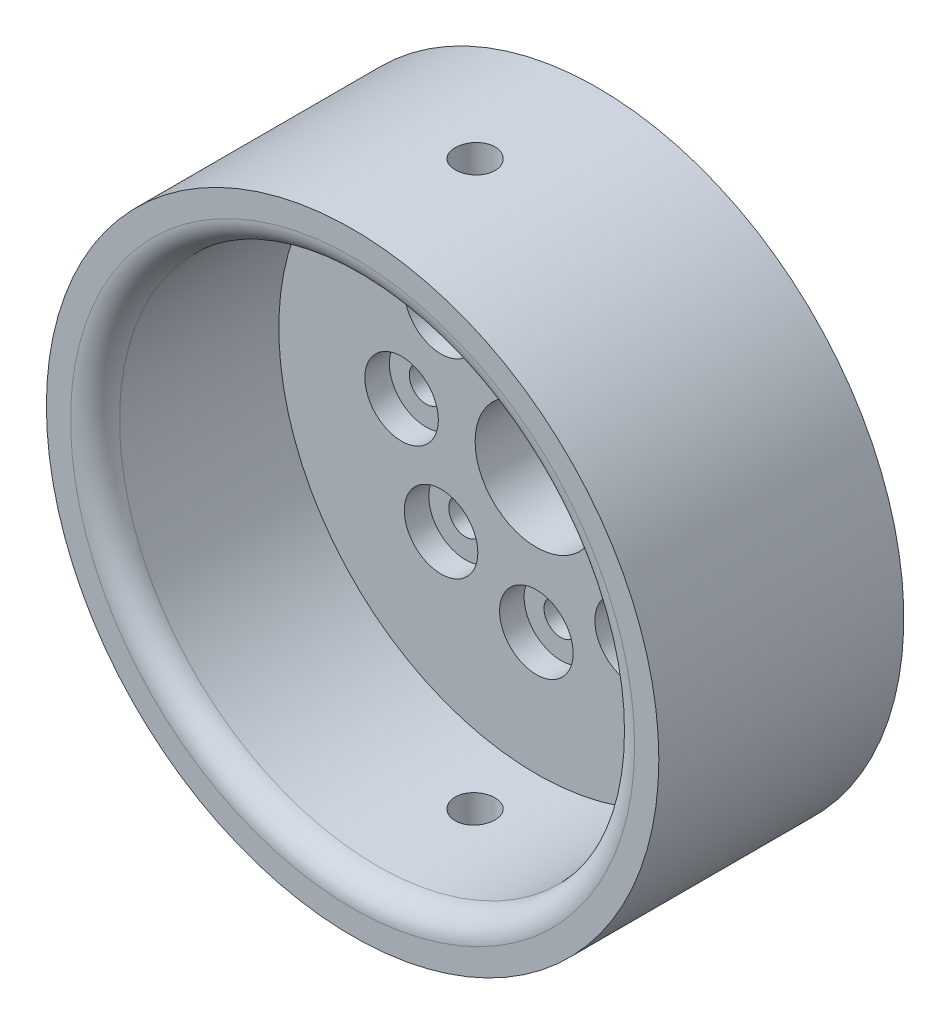
SolidWorks part; units mm, degrees
ref_plane "Front Plane" through (0, 0, 0) normal (0, 0, 1) x (1, 0, 0)
ref_plane "Top Plane" through (0, 0, 0) normal (0, 1, 0) x (1, 0, 0)
ref_plane "Right Plane" through (0, 0, 0) normal (1, 0, 0) x (0, 0, -1)
sketch "Sketch1" plane through (0, 0, 0) normal (0, 0, 1) x (1, 0, 0)
  circle A0 centre (0, 0) radius 20.15
  circle A1 centre (0, 0) radius 25
  dimension "D1" = 40.3
  dimension "D2" = 50
extrude "Boss-Extrude1" add sketch "Sketch1" along normal blind 10
sketch "Sketch2" plane through (0, 0, 0) normal (0, 0, -1) x (-1, 0, 0)
  circle A0 centre (0, 0) radius 11
  circle A1 centre (-11, 0) radius 1.375
  circle A2 centre (-7.7782, 7.7782) radius 1.375
  circle A3 centre (0, 11) radius 1.375
  circle A4 centre (7.7782, 7.7782) radius 1.375
  circle A5 centre (11, 0) radius 1.375
  circle A6 centre (7.7782, -7.7782) radius 1.375
  circle A7 centre (0, -11) radius 1.375
  circle A8 centre (-7.7782, -7.7782) radius 1.375
  circle A9 centre (0, 0) radius 5
  circle A10 centre (0, 0) radius 25
  point P26 (0, 0)
  circle M7 centre (0, 0) radius 25
  circle M8 centre (0, 0) radius 20.15
  dimension "D5" = 22
  dimension "D6" = 2.75
  dimension "D8" = 10
  dimension "D7" = 8
extrude "Boss-Extrude2" add sketch "Sketch2" along normal blind 5 contours A8 A0 A1 A2 A3 A4 A5 A6 A7 M8 | A8 A0 A7 A6 A5 A4 A3 A2 A1 A9 | M7 M8
sketch "Sketch3" plane through (0, 0, 0) normal (0, 0, 1) x (1, 0, 0)
  circle A0 centre (0, 11) radius 3
  circle A1 centre (7.7782, 7.7782) radius 3
  circle A2 centre (11, 0) radius 3
  circle A3 centre (7.7782, -7.7782) radius 3
  circle A4 centre (0, -11) radius 3
  circle A5 centre (-7.7782, -7.7782) radius 3
  circle A6 centre (-11, 0) radius 3
  circle A7 centre (-7.7782, 7.7782) radius 3
  point P19 (0, 0)
  dimension "D1" = 6
  dimension "D2" = 8
extrude "Cut-Extrude1" cut sketch "Sketch3" against normal blind 2
sketch "Sketch4" plane through (0, 0, 0) normal (0, 1, 0) x (1, 0, 0)
  line L0 (-20.15, 0) -> (20.15, 0) construction
  circle A0 centre (0, -5) radius 1.625
  dimension "D1" = 3.25
  dimension "D2" = 5
extrude "Cut-Extrude2" cut sketch "Sketch4" against normal blind 33 and the other way blind 38
sketch "Sketch5" plane through (0, 0, 10) normal (0, 0, 1) x (1, 0, 0)
  circle A0 centre (0, 0) radius 21.025
  dimension "D1" = 42.05
extrude "Cut-Extrude3" cut sketch "Sketch5" against normal blind 10
sketch "Sketch6" plane through (0, 0, 10) normal (0, 0, 1) x (1, 0, 0)
  circle A0 centre (0, 0) radius 21.025
  circle A1 centre (0, 0) radius 25
extrude "Boss-Extrude3" add sketch "Sketch6" along normal blind 5
fillet "Fillet1" radius 2 1 edges at (21.025, 0, 15)
